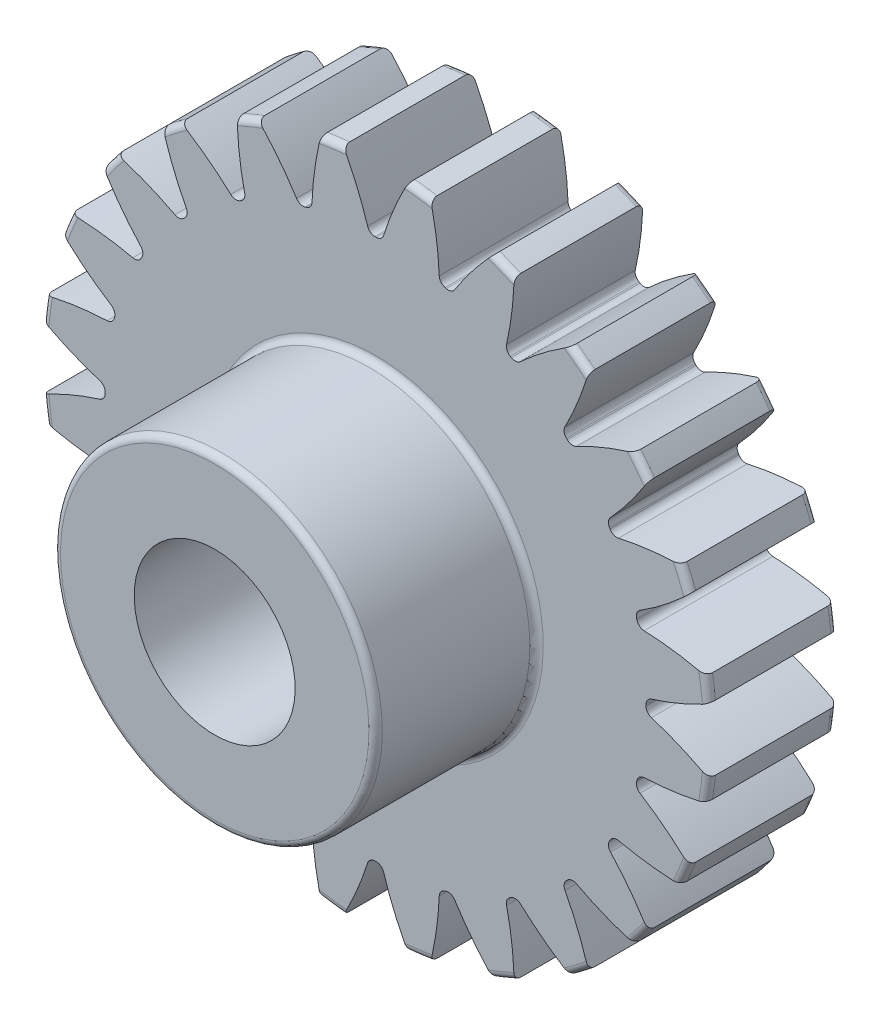
SolidWorks part; units mm, degrees
ref_plane "Front Plane" through (0, 0, 0) normal (0, 0, 1) x (1, 0, 0)
ref_plane "Top Plane" through (0, 0, 0) normal (0, 1, 0) x (1, 0, 0)
ref_plane "Right Plane" through (0, 0, 0) normal (1, 0, 0) x (0, 0, -1)
sketch "Sketch1" plane through (0, 0, 0) normal (0, 0, 1) x (1, 0, 0)
  line L0 (-304.8, 0) -> (304.8, 0) construction
  circle A0 centre (0, 0) radius 10.4 construction
  circle A1 centre (0, 0) radius 9.6 construction
  circle A2 centre (0, 0) radius 8.4 construction
  circle A3 centre (0, 0) radius 5 construction
  circle A4 centre (0, 0) radius 2.5 construction
  dimension "D2" = 0.8
  dimension "D3" = 2
sketch "Sketch2" plane through (0, 0, 0) normal (1, 0, 0) x (0, 0, -1)
  line L0 (0, 0) -> (-4, 0) construction
  line L1 (-4, 0) -> (-9, 0) construction
  dimension "Overall Width" = 9
  dimension "Face Width" = 4
sketch "Sketch4" plane through (0, 0, 0) normal (1, 0, 0) x (0, 0, -1)
  line L0 (-9, 2.5) -> (-9, 5)
  line L1 (-9, 5) -> (-4, 5)
  line L2 (-4, 5) -> (-4, 10.4)
  line L3 (-4, 10.4) -> (0, 10.4)
  line L4 (0, 10.4) -> (0, 2.5)
  line L5 (-4, 5) -> (-4, 0) construction
  line L6 (0, 10.4) -> (0, -10.4) construction
  line L7 (-4, 5) -> (0, 5) construction
  line L12 (-9, 2.5) -> (0, 2.5)
revolve "Revolve1" add sketch "Sketch4" angle 360 about L1
fillet "Fillet2" radius 0.208 4 edges at (0, 5, 9) (0, 5, 4) (0, 10.4, 4) (0, 10.4, 0)
sketch "Sketch7" plane through (0, 0, 4) normal (0, 0, 1) x (1, 0, 0)
  line L0 (0, 0) -> (0, 10.4) construction
  line L1 (0.6279, 9.5794) -> (0.969, 10.3548) construction
  line L3 (1.3575, 10.311) -> (1.2531, 9.5179) construction
  line L4 (1.2531, 9.5179) -> (1.0964, 8.3281) construction
  line L5 (0, 0) -> (1.0964, 8.3281) construction
  line L6 (0.6279, 9.5794) -> (0, 0) construction
  line L7 (0.6279, 9.5794) -> (0.6802, 10.3777) construction
  line L8 (0.6279, 9.5794) -> (0, 0) construction
  circle A0 centre (0, 0) radius 10.4 construction
  arc A1 (-0.0197, 8.4) -> (0.0197, 8.4) centre (0, 0) cw
  circle A2 centre (0, 0) radius 8.4 construction
  arc A3 (-0.6279, 9.5794) -> (0.6279, 9.5794) centre (0, 0) cw construction
  circle A4 centre (0, 0) radius 9.6 construction
  arc A5 (1.7039, 10.2595) -> (1.0095, 10.3509) centre (0, 0) ccw construction
  arc A6 (0.6279, 9.5794) -> (1.8729, 9.4155) centre (0, 0) cw construction
  arc A7 (-1.0095, 10.3509) -> (1.0095, 10.3509) centre (0, 0) cw
  arc A8 (0.2494, 8.5686) -> (1.0095, 10.3509) centre (9.4149, 5.7131) cw
  arc A9 (-0.2494, 8.5686) -> (-1.0095, 10.3509) centre (-9.4149, 5.7131) ccw
  arc A10 (-0.0197, 8.4) -> (-0.2494, 8.5686) centre (-0.0202, 8.64) cw
  arc A11 (0.0197, 8.4) -> (0.2494, 8.5686) centre (0.0202, 8.64) ccw
  point P26 (-0.1979, 8.3977)
  point P29 (0.1979, 8.3977)
  dimension "D4" = 0.24
  dimension "D5" = 9.6
  dimension "D3" = 20
  dimension "D1" = 2.5133
  dimension "D2" = 1.2566
extrude "Cut-Extrude2" cut sketch "Sketch7" against normal through all
pattern_circular "CirPattern1" count 24 over 360 about axis through (0, 0, 0) along (0, 0, 1) of "Cut-Extrude2"
equation "\"D1@Sketch1\"=2.5*(\"Pitch Dia.@Sketch1\"/\"Number of Teeth@Sketch1\")"
equation "\"D1@CirPattern1\"=\"Number of Teeth@Sketch1\""
equation "\"D1@Fillet2\"=\"OD@Sketch1\"*.01"
equation "\"D1@Sketch7\"=3.14159*(\"Pitch Dia.@Sketch1\"/\"Number of Teeth@Sketch1\")"
equation "\"D2@Sketch7\"=\"D1@Sketch7\"/2"
equation "\"D4@Sketch7\"=\"D1@Sketch7\"*.0955"
equation "\"D5@Sketch7\"=\"Pitch Dia.@Sketch1\"/2"
